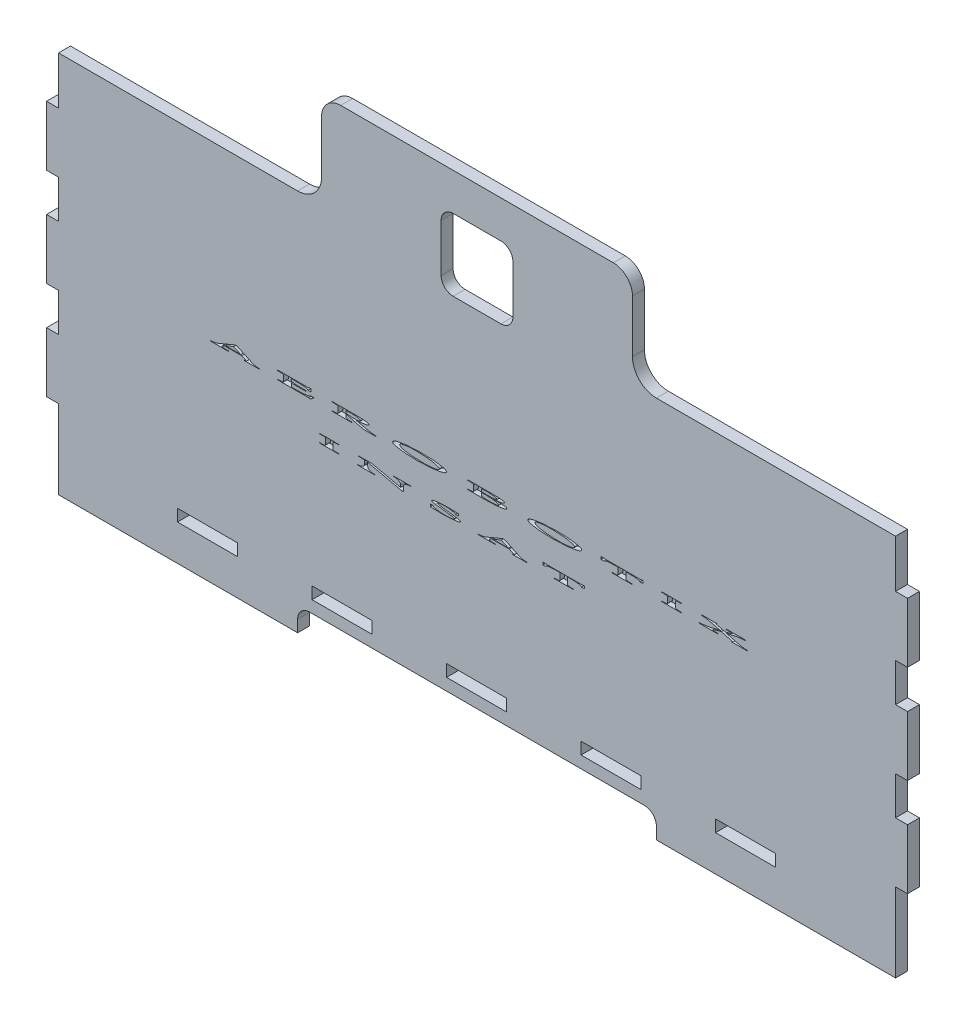
SolidWorks part; units mm, degrees
ref_plane "Front Plane" through (0, 0, 0) normal (0, 0, 1) x (1, 0, 0)
ref_plane "Top Plane" through (0, 0, 0) normal (0, 1, 0) x (1, 0, 0)
ref_plane "Right Plane" through (0, 0, 0) normal (1, 0, 0) x (0, 0, -1)
sketch "Sketch1" plane through (0, 0, 0) normal (0, 0, 1) x (1, 0, 0)
  line L0 (75, -100) -> (175, -100)
  line L1 (-175, -100) -> (-75, -100)
  line L2 (-175, -100) -> (-175, 60)
  line L3 (-57, 100) -> (57, 100)
  line L4 (175, -100) -> (175, 60)
  line L5 (-175, -100) -> (105, 60) construction
  line L6 (-105, 60) -> (175, -100) construction
  line L9 (175, 60) -> (75, 60)
  line L10 (65, 92) -> (65, 70)
  line L13 (-175, 60) -> (-75, 60)
  line L14 (-65, 92) -> (-65, 70)
  line L15 (-70, -90) -> (70, -90)
  line L16 (-75, -95) -> (-75, -100)
  line L18 (75, -95) -> (75, -100)
  line L20 (-15, 84.3775) -> (15, 84.3775)
  line L21 (-15, 84.3775) -> (-15, 54.3775)
  line L22 (-15, 54.3775) -> (15, 54.3775)
  line L23 (15, 84.3775) -> (15, 54.3775)
  line L24 (-15, 84.3775) -> (15, 54.3775) construction
  line L25 (-15, 54.3775) -> (15, 84.3775) construction
  arc A0 (-75, 60) -> (-65, 70) centre (-75, 70) ccw
  arc A1 (75, 60) -> (65, 70) centre (75, 70) cw
  arc A2 (-70, -90) -> (-75, -95) centre (-70, -95) ccw
  arc A3 (70, -90) -> (75, -95) centre (70, -95) cw
  arc A4 (-57, 100) -> (-65, 92) centre (-57, 92) ccw
  arc A5 (57, 100) -> (65, 92) centre (57, 92) cw
  point P0 (0, 0)
  point P18 (-65, 60)
  point P21 (65, 60)
  point P24 (-75, -90)
  point P27 (75, -90)
  point P32 (0, 69.3775)
  dimension "D7" = 10
  dimension "D11" = 5
  dimension "D2" = 8
  dimension "D3" = 30
  dimension "D4" = 30
  dimension "D5" = 110
  dimension "D6" = 110
  dimension "D8" = 10
  dimension "D9" = 150
  dimension "D10" = 100
  dimension "D12" = 50
extrude "Boss-Extrude1" add sketch "Sketch1" along normal blind 5
sketch "Sketch3" plane through (175, 0, 0) normal (1, 0, 0) x (0, 0, -1)
  line L0 (-5, -100) -> (-5, 60) construction
  line L1 (-5, 40) -> (0, 40)
  line L2 (-5, 40) -> (-5, 15)
  line L3 (-5, 15) -> (0, 15)
  line L4 (0, 40) -> (0, 15)
  line L5 (0, -100) -> (0, 60) construction
  line L7 (-5, -1) -> (0, -1)
  line L8 (-5, -1) -> (-5, -26)
  line L9 (-5, -26) -> (0, -26)
  line L10 (0, -1) -> (0, -26)
  line L11 (-5, -42) -> (0, -42)
  line L12 (-5, -42) -> (-5, -67)
  line L13 (-5, -67) -> (0, -67)
  line L14 (0, -42) -> (0, -67)
  line L15 (-5, 70) -> (0, 70) construction
  dimension "D1" = 30
  dimension "D2" = 25
  dimension "D3" = 25
  dimension "D4" = 25
  dimension "D5" = 16
  dimension "D6" = 16
extrude "Boss-Extrude2" add sketch "Sketch3" along normal blind 5
mirror "Mirror1" about plane through (0, 0, 0) normal (1, 0, 0) of "Boss-Extrude2"
sketch "Sketch4" plane through (0, 0, 5) normal (0, 0, 1) x (1, 0, 0)
  line L0 (-175, -67) -> (-175, -100) construction
  line L1 (124.75, -80) -> (99.75, -80)
  line L2 (124.75, -80) -> (124.75, -85)
  line L3 (124.75, -85) -> (99.75, -85)
  line L4 (99.75, -80) -> (99.75, -85)
  line L5 (68.5, -85) -> (43.5, -85)
  line L6 (68.5, -85) -> (68.5, -80)
  line L7 (68.5, -80) -> (43.5, -80)
  line L8 (43.5, -85) -> (43.5, -80)
  line L9 (12.25, -80) -> (-12.75, -80)
  line L10 (12.25, -80) -> (12.25, -85)
  line L11 (12.25, -85) -> (-12.75, -85)
  line L12 (-12.75, -80) -> (-12.75, -85)
  line L13 (-44, -80) -> (-69, -80)
  line L14 (-44, -80) -> (-44, -85)
  line L15 (-44, -85) -> (-69, -85)
  line L16 (-69, -80) -> (-69, -85)
  line L17 (-100.25, -80) -> (-125.25, -80)
  line L18 (-100.25, -80) -> (-100.25, -85)
  line L19 (-100.25, -85) -> (-125.25, -85)
  line L20 (-125.25, -80) -> (-125.25, -85)
  line L26 (75, -100) -> (175, -100) construction
  line L27 (-175, -100) -> (-75, -100) construction
  point P20 (68.5, -82.5)
  dimension "D1" = 25
  dimension "D2" = 25
  dimension "D3" = 25
  dimension "D4" = 25
  dimension "D5" = 25
  dimension "D6" = 5
  dimension "D7" = 5
  dimension "D8" = 5
  dimension "D9" = 5
  dimension "D10" = 5
  dimension "D11" = 31.25
  dimension "D12" = 31.25
  dimension "D13" = 31.25
  dimension "D14" = 31.25
  dimension "D15" = 49.75
  dimension "D16" = 15
  dimension "D17" = 15
  dimension "D18" = 15
  dimension "D19" = 15
  dimension "D20" = 15
extrude "Cut-Extrude1" cut sketch "Sketch4" against normal blind 10
fillet "Fillet1" radius 5 4 edges at (15, 54.3775, 2.5) (15, 84.3775, 2.5) (-15, 84.3775, 2.5) (-15, 54.3775, 2.5)
sketch "Sketch5" plane through (0, 0, 5) normal (0, 0, 1) x (1, 0, 0)
  line L0 (305.9471, 576.7801) -> (1417.2804, 576.7801) construction
  line L1 (28.0568, 102.4882) -> (689.3902, 102.4882) construction
sketch "Sketch8" plane through (0, 0, 5) normal (0, 0, 1) x (1, 0, 0)
  text T0 "<b>AEROBOTIX</b>\r\n\r\n   INSAT" font "Footlight MT Light" height 3.5
extrude "Cut-Extrude3" cut sketch "Sketch8" against normal blind 2
